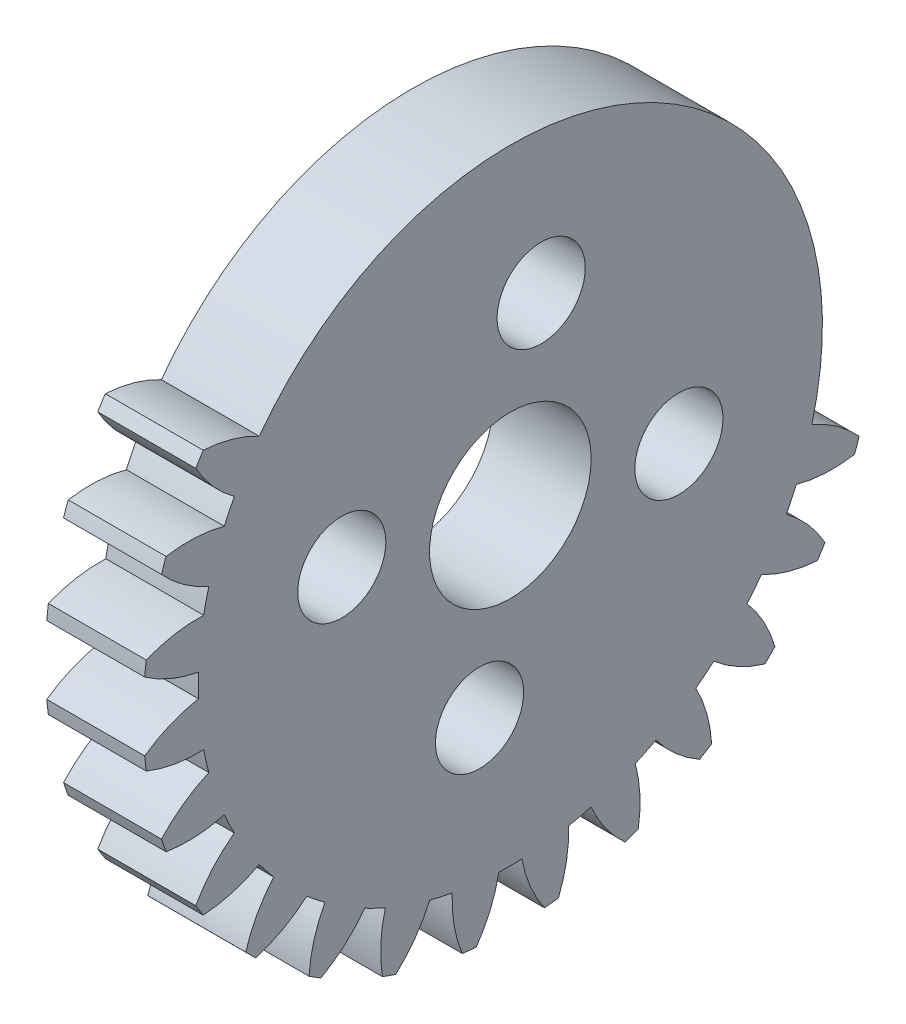
SolidWorks part; units mm, degrees
ref_plane "Plane1" through (0, 0, 0) normal (0, 0, 1) x (1, 0, 0)
ref_plane "Plane2" through (0, 0, 0) normal (0, 1, 0) x (1, 0, 0)
ref_plane "Plane3" through (0, 0, 0) normal (1, 0, 0) x (0, 0, -1)
sketch "HoldingSke" plane through (0, 0, 0) normal (0, 1, 0) x (1, 0, 0)
  line L0 (0, 0) -> (0.8829, -0.4695)
  line L1 (-15, 0) -> (100, 0) construction
  line L2 (0, 0) -> (-2.1039, 2.3779)
  line L3 (0, 0) -> (-11.863, 4.5341)
  line L4 (0, 0) -> (7.6251, 4.0544)
  line L5 (0, 0) -> (-46.8476, -17.4728)
  line L6 (0, 0) -> (-8.2896, -5.593)
  line L7 (-2.1039, 2.3779) -> (8.6586, 51.2059)
  line L8 (-76.2, 54.61) -> (-75.2, 54.61)
  line L9 (-71.009, 38.7566) -> (-53.1078, 45.2721)
  line L10 (-76.2, 71.12) -> (104.1128, 71.12)
  line L11 (0, 0) -> (-10, 0)
  line L12 (-76.2, 101.6) -> (-76.162, 101.6)
  line L13 (24.9733, 27.94) -> (52.9518, 28.4284)
  line L14 (24.9733, 27.94) -> (24.9743, 27.94)
  line L15 (24.9733, 27.94) -> (100.4006, 29.5858)
  line L16 (-63.627, -1) -> (-12.827, -1)
  circle A0 centre (0, 0) radius 3
  circle A1 centre (0, 0) radius 12.749
  circle A2 centre (0, 0) radius 37.5
  circle A3 centre (0, 0) radius 3
  dimension "MHD" = 25.498
  dimension "Hub_dia" = 75
  dimension "Bore" = 6
  dimension "MBD" = 6
  dimension "Num_teeth" = 28
  dimension "Pitch" = 1
  dimension "Overall_len" = 50
  dimension "Show_teeth" = 28
  dimension "Thickness" = 10
  dimension "OAL" = 50.0001
  dimension "T_dim" = 1
  dimension "Ap" = 20
  dimension "H" = 19.05
  dimension "Pitch_radius" = 180.3128
  dimension "Width" = 10
  dimension "Backlash" = 0.038
  dimension "Addendum_fac" = 1
  dimension "Dedendum_fac" = 1.25
  dimension "Clearance_fac" = 0.25
  dimension "Dedendum_add" = 0.001
  dimension "Module" = 1
sketch "BasProSke" plane through (0, 0, 0) normal (0, 1, 0) x (1, 0, 0)
  line L0 (-10, 0) -> (60, 0) construction
  line L1 (0, 0) -> (0, 15)
  line L2 (0, 0) -> (10, 0)
  line L3 (10, 0) -> (10, 15)
  line L4 (10, 15) -> (0, 15)
  dimension "Thickness" = 10
  dimension "Diameter" = 30
revolve "Base-Revolve" add sketch "BasProSke" angle 360 about L0
sketch "TooCutSke" plane through (0, 0, 0) normal (1, 0, 0) x (0, 0, -1)
  line L1 (0, 0) -> (0, 107) construction
  line L2 (0, 0) -> (-0.8515, 13.9741) construction
  line L3 (0, 0) -> (-3.1309, 27.7873) construction
  line L4 (-0.8515, 13.9741) -> (-1.5654, 13.8936) construction
  arc A0 (0.4713, 12.7403) -> (-0.4713, 12.7403) centre (0, 0) ccw
  arc A1 (1.4098, 14.9591) -> (-1.4098, 14.9591) centre (0, 0) ccw
  circle A2 centre (0, 0) radius 14 construction
  circle A3 centre (0, 0) radius 13.1557 construction
  arc A4 (-0.4713, 12.7403) -> (-1.4098, 14.9591) centre (-5.9775, 11.7193) ccw
  arc A5 (1.4098, 14.9591) -> (0.4713, 12.7403) centre (5.9775, 11.7193) ccw
  dimension "Root_dia" = 25.498
  dimension "Overcut_dia" = 30.0508
  dimension "Pitch_dia" = 28
  dimension "Base_dia" = 26.3114
  dimension "Flank_rad" = 5.6
  dimension "Half_ang" = 6.429
  dimension "Half_CT" = 0.7185
extrude "ToothCut" cut sketch "TooCutSke" along normal through all
fillet "Breaks" [suppressed] radius 0.02
fillet "RootFillets" [suppressed] radius 0.251
pattern_circular "TeethCuts" count 28 every 12.857 about axis through (-10, 0, 0) along (1, 0, 0) of "ToothCut", "RootFillets", "Breaks"
sketch "HubNeaOneSke" plane through (0, 0, 0) normal (-1, 0, 0) x (0, 0, 1)
  circle A0 centre (0, 0) radius 12.749
  dimension "Diameter" = 25.498
extrude "HubNearOne" [suppressed] add sketch "HubNeaOneSke" along normal blind 40.0001
sketch "HubNeaBotSke" plane through (0, 0, 0) normal (-1, 0, 0) x (0, 0, 1)
  circle A0 centre (0, 0) radius 12.749
  dimension "Diameter" = 25.498
extrude "HubNearBoth" [suppressed] add sketch "HubNeaBotSke" along normal blind 20
ref_plane "FarPln" through (10, 0, 0) normal (1, 0, 0) x (0, 0, -1)
sketch "HubFarSke" plane through (10, 0, 0) normal (1, 0, 0) x (0, 0, -1)
  circle A0 centre (0, 0) radius 12.749
  dimension "Diameter" = 25.498
extrude "HubFar" [suppressed] add sketch "HubFarSke" along normal blind 20
sketch "BorSke" plane through (0, 0, 0) normal (1, 0, 0) x (0, 0, -1)
  circle A0 centre (0, 0) radius 3.3
  dimension "Diameter" = 6.6
extrude "Bore" cut sketch "BorSke" along normal mid plane 100.0001
sketch "KeySke" plane through (0, 0, 0) normal (1, 0, 0) x (0, 0, -1)
  line L0 (-1, 0) -> (-1, 4)
  line L1 (-1, 4) -> (1, 4)
  line L2 (1, 4) -> (1, 0)
  line L3 (0, 0) -> (0, 34) construction
  line L4 (-1, 0) -> (1, 0)
  dimension "Offset" = 4
  dimension "Width" = 2
extrude "Keyway" [suppressed] cut sketch "KeySke" along normal mid plane 100.0001
pattern_circular "Keyway2" [suppressed] count 2 every 90 about axis through (-10, 0, 0) along (1, 0, 0)
sketch "ｽｹｯﾁ1" plane through (10, 0, 0) normal (1, 0, 0) x (0, 0, -1)
  circle A0 centre (0, 0) radius 15
extrude "ｶｯﾄ - 押し出し1" cut sketch "ｽｹｯﾁ1" against normal blind 6
sketch "ｽｹｯﾁ2" plane through (0, 0, 0) normal (-1, 0, 0) x (0, 0, 1)
  line L0 (-12.5257, -2.3755) -> (0, 0) construction
  line L1 (0, 0) -> (10.2546, 7.5749) construction
  line L2 (-12.5257, -2.3755) -> (-14.7373, -2.7949)
  line L3 (10.2546, 7.5749) -> (12.0652, 8.9124)
  arc A0 (10.2546, 7.5749) -> (-12.5257, -2.3755) centre (0, 0) ccw
  arc A1 (12.0652, 8.9124) -> (-14.7373, -2.7949) centre (0, 0) ccw
  arc A2 (-14.9352, -1.3929) -> (-14.8707, -1.9654) centre (0, 0) ccw construction
  point P9 (12.0652, 8.9124)
  point P10 (12.2021, 9.1059)
  point P12 (12.2564, 9.1059)
  point P15 (-14.6949, -2.7868)
  point P16 (0, 0)
  point P18 (-14.7701, -2.6161)
extrude "ｶｯﾄ - 押し出し2" cut sketch "ｽｹｯﾁ2" against normal blind 10
sketch "ｽｹｯﾁ3" plane through (4, 0, 0) normal (1, 0, 0) x (0, 0, -1)
  circle A0 centre (-6.8858, 1.2591) radius 1.8
  circle A1 centre (1.2591, 6.8858) radius 1.8
  circle A2 centre (6.8858, -1.2591) radius 1.8
  circle A3 centre (-1.2591, -6.8858) radius 1.8
  dimension "D1" = 3.6
extrude "ｶｯﾄ - 押し出し3" cut sketch "ｽｹｯﾁ3" against normal blind 10
equation "' \"Module@HoldingSke\" = 6.35"
equation "' \"Num_teeth@HoldingSke\" = 12"
equation "' \"Ap@HoldingSke\" =  20"
equation "' \"Ap@HoldingSke\" = 20"
equation "' \"Width@HoldingSke\" = 0.5 * 25.4"
equation "' \"Hub_dia@HoldingSke\"= 1 * 25.4"
equation "' \"Hub_dia@HoldingSke\" = 1 * 25.4"
equation "' \"Overall_len@HoldingSke\" = 1.0 * 25.4"
equation "' \"Bore@HoldingSke\" = 0.75 * 25.4"
equation "' \"T_dim@HoldingSke\" = 0.1 * 25.4"
equation "' \"Width@KeySke\" = 0.25 * 25.4"
equation "' \"Show_teeth@HoldingSke\" = 13"
equation "' \"Backlash@HoldingSke\" = 0.009 * 25.4"
equation "' \"Addendum_fac@HoldingSke\" = 1.0"
equation "' \"Dedendum_fac@HoldingSke\" = 1.25"
equation "' \"Dedendum_add@HoldingSke\" = 0.00005 * 25.4"
equation "' \"Clearance_fac@HoldingSke\" = 0.25"
equation "\"Pitch@HoldingSke\" = 1 / \"Module@HoldingSke\""
equation "\"Overcut_dia@TooCutSke\" = (\"Num_teeth@HoldingSke\" + 2 * \"Addendum_fac@HoldingSke\") / \"Pitch@HoldingSke\" + 0.002 * 25.4"
equation "\"Pitch_dia@TooCutSke\" = \"Num_teeth@HoldingSke\" / \"Pitch@HoldingSke\""
equation "\"Base_dia@TooCutSke\" = \"Num_teeth@HoldingSke\" / \"Pitch@HoldingSke\" * cos((\"Ap@HoldingSke\"  * 3.14159265 / 180))"
equation "\"Root_dia@TooCutSke\" = (\"Num_teeth@HoldingSke\" + 2) / \"Pitch@HoldingSke\" - 2 * (\"Addendum_fac@HoldingSke\" + \"Dedendum_fac@HoldingSke\") / \"Pitch@HoldingSke\" - \"Dedendum_add@HoldingSke\" * 2"
equation "\"Half_ang@TooCutSke\" = 180 / \"Num_teeth@HoldingSke\""
equation "\"Half_CT@TooCutSke\" = \"Num_teeth@HoldingSke\" / \"Pitch@HoldingSke\" * sin((3.14159265 / 2 / \"Num_teeth@HoldingSke\")) / 2 - 7 * \"Backlash@HoldingSke\" / 4"
equation "\"Flank_rad@TooCutSke\" = \"Num_teeth@HoldingSke\" / \"Pitch@HoldingSke\" / 5"
equation "\"Radius@RootFillets\" = \"Clearance_fac@HoldingSke\" / \"Pitch@HoldingSke\" + \"Dedendum_add@HoldingSke\""
equation "\"Break_rad@Breaks\" = 0.02 / \"Pitch@HoldingSke\""
equation "\"Thickness@HoldingSke\" = \"Width@HoldingSke\""
equation "\"OAL@HoldingSke\" = \"Thickness@HoldingSke\""
equation "\"MHD@HoldingSke\" = (\"Num_teeth@HoldingSke\" + 2) / \"Pitch@HoldingSke\" - 2 * (\"Addendum_fac@HoldingSke\" + \"Dedendum_fac@HoldingSke\")  / \"Pitch@HoldingSke\" - \"Dedendum_add@HoldingSke\" * 2"
equation "\"MBD@HoldingSke\" = (\"Num_teeth@HoldingSke\" + 2) / \"Pitch@HoldingSke\" - 2 * (\"Addendum_fac@HoldingSke\" + \"Dedendum_fac@HoldingSke\")  / \"Pitch@HoldingSke\" - \"Dedendum_add@HoldingSke\" * 2 - 0.002 * 25.4"
equation "\"MHD@HoldingSke\" = ((sgn( \"MHD@HoldingSke\" - \"Hub_dia@HoldingSke\" )-1)*( \"MHD@HoldingSke\" - \"Hub_dia@HoldingSke\" ))/-2+ \"Hub_dia@HoldingSke\""
equation "\"MBD@HoldingSke\" = ((sgn( \"MBD@HoldingSke\" - \"Bore@HoldingSke\" )-1)*( \"MBD@HoldingSke\" - \"Bore@HoldingSke\" ))/-2+ \"Bore@HoldingSke\""
equation "\"OAL@HoldingSke\" = ((sgn( \"OAL@HoldingSke\" - \"Overall_len@HoldingSke\" )+1)*( \"OAL@HoldingSke\" - \"Overall_len@HoldingSke\" ))/2 + \"Overall_len@HoldingSke\" + 0.000002 * 25.4"
equation "\"Num_teeth@TeethCuts\" = int( \"Show_teeth@HoldingSke\" ) + 1"
equation "\"Num_teeth@TeethCuts\" = ((sgn( \"Num_teeth@TeethCuts\" - \"Num_teeth@HoldingSke\" )-1)*( \"Num_teeth@TeethCuts\" - \"Num_teeth@HoldingSke\" ))/-2+ \"Num_teeth@HoldingSke\""
equation "\"Num_teeth@TeethCuts\" = ((sgn( \"Num_teeth@TeethCuts\" - 2.0)+1)*( \"Num_teeth@TeethCuts\" - 2.0))/2 +2.0"
equation "\"Angle@TeethCuts\" = 360.0 / \"Num_teeth@HoldingSke\""
equation "\"Diameter@BasProSke\" = (\"Num_teeth@HoldingSke\" + 2 * \"Addendum_fac@HoldingSke\") / \"Pitch@HoldingSke\""
equation "\"Thickness@BasProSke\"  = \"Thickness@HoldingSke\""
equation "' \"Fillet_rad@BasProSke\" =  \"Thickness@HoldingSke\" * 0.05"
equation "' \"Fillet_rad@BasProSke\" = \"Thickness@HoldingSke\" * 0.05"
equation "\"MHD@HoldingSke\" = ((sgn( \"MHD@HoldingSke\" - \"Root_dia@TooCutSke\" )-1)*( \"MHD@HoldingSke\" - \"Root_dia@TooCutSke\" ))/-2+ \"Root_dia@TooCutSke\""
equation "\"Diameter@HubNeaOneSke\" = \"MHD@HoldingSke\""
equation "\"Length@HubNearOne\" = \"OAL@HoldingSke\" - \"Thickness@BasProSke\""
equation "\"Diameter@HubNeaBotSke\" = \"MHD@HoldingSke\""
equation "\"Length@HubNearBoth\" = ( \"OAL@HoldingSke\" - \"Thickness@BasProSke\" ) / 2.0"
equation "\"Thickness@FarPln\" = \"Thickness@BasProSke\""
equation "\"Diameter@HubFarSke\" = \"MHD@HoldingSke\""
equation "\"Length@HubFar\" = ( \"OAL@HoldingSke\" - \"Thickness@BasProSke\" ) / 2.0"
equation "\"Diameter@BorSke\"=6.6"
equation "\"D1@Bore\" = \"OAL@HoldingSke\" * 2.0"
equation "\"D1@Keyway\" = \"OAL@HoldingSke\" * 2.0"
equation "\"Offset@KeySke\" = \"T_dim@HoldingSke\" + \"MBD@HoldingSke\" / 2.0"
